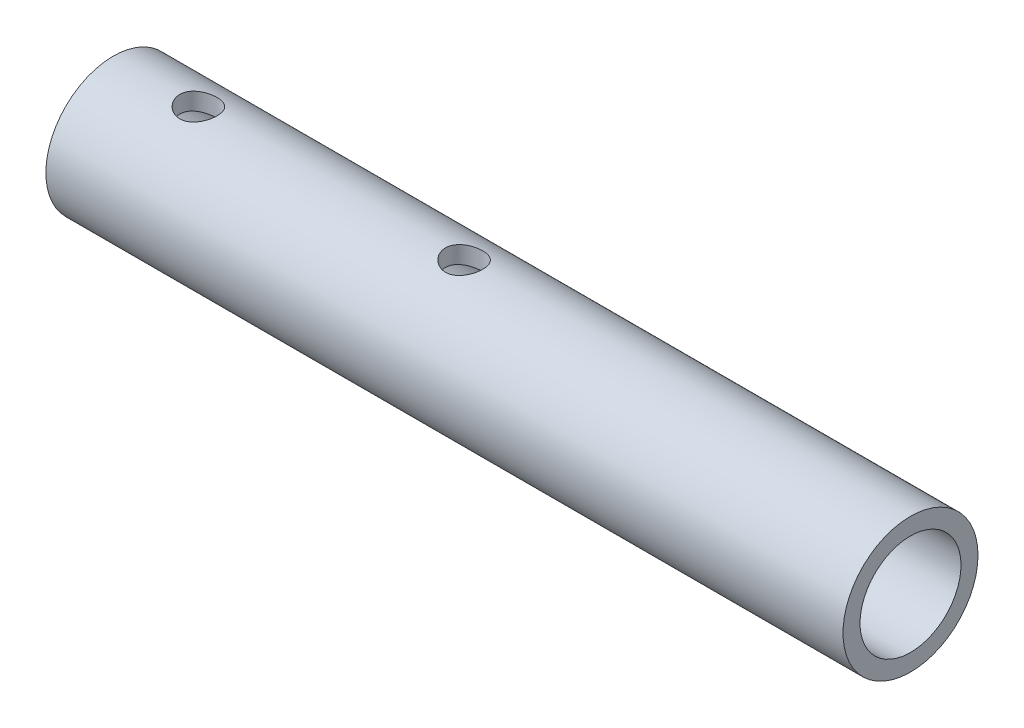
SolidWorks part; units mm, degrees
material "1060 Alloy"
ref_plane "Front Plane" through (0, 0, 0) normal (0, 0, 1) x (1, 0, 0)
ref_plane "Top Plane" through (0, 0, 0) normal (0, 1, 0) x (1, 0, 0)
ref_plane "Right Plane" through (0, 0, 0) normal (1, 0, 0) x (0, 0, -1)
sketch "Sketch1" plane through (0, 0, 0) normal (1, 0, 0) x (0, 0, -1)
  circle A0 centre (0, 0) radius 6.35
  circle A1 centre (0, 0) radius 4.75
  dimension "D1" = 12.7
  dimension "D2" = 1.6
extrude "Boss-Extrude1" add sketch "Sketch1" along normal blind 75
ref_plane "Plane1" through (0, 6.35, 0) normal (0, 1, 0) x (1, 0, 0)
sketch "Sketch2" plane through (0, 6.35, 0) normal (0, 1, 0) x (1, 0, 0)
  line L0 (0, 0) -> (75, 0) construction
  line L1 (75, -6.35) -> (75, 6.35) construction
  line L2 (0, 6.35) -> (0, -6.35) construction
  circle A0 centre (8, 0) radius 1.75
  circle A1 centre (33, 0) radius 1.75
  dimension "D1" = 3.5
  dimension "D3" = 25
  dimension "D2" = 8
extrude "Cut-Extrude1" cut sketch "Sketch2" against normal up to surface (1.9341 mm away)
sketch "Sketch3" plane through (75, 0, 0) normal (1, 0, 0) x (0, 0, -1)
  line L0 (-2.5, 5.8372) -> (2.5, 5.8372)
  circle A0 centre (0, 0) radius 6.35 construction
  arc A1 (2.5, 5.8372) -> (-2.5, 5.8372) centre (0, 0) ccw
  dimension "D1" = 5
extrude "Cut-Extrude2" [suppressed] cut sketch "Sketch3" against normal blind 40
